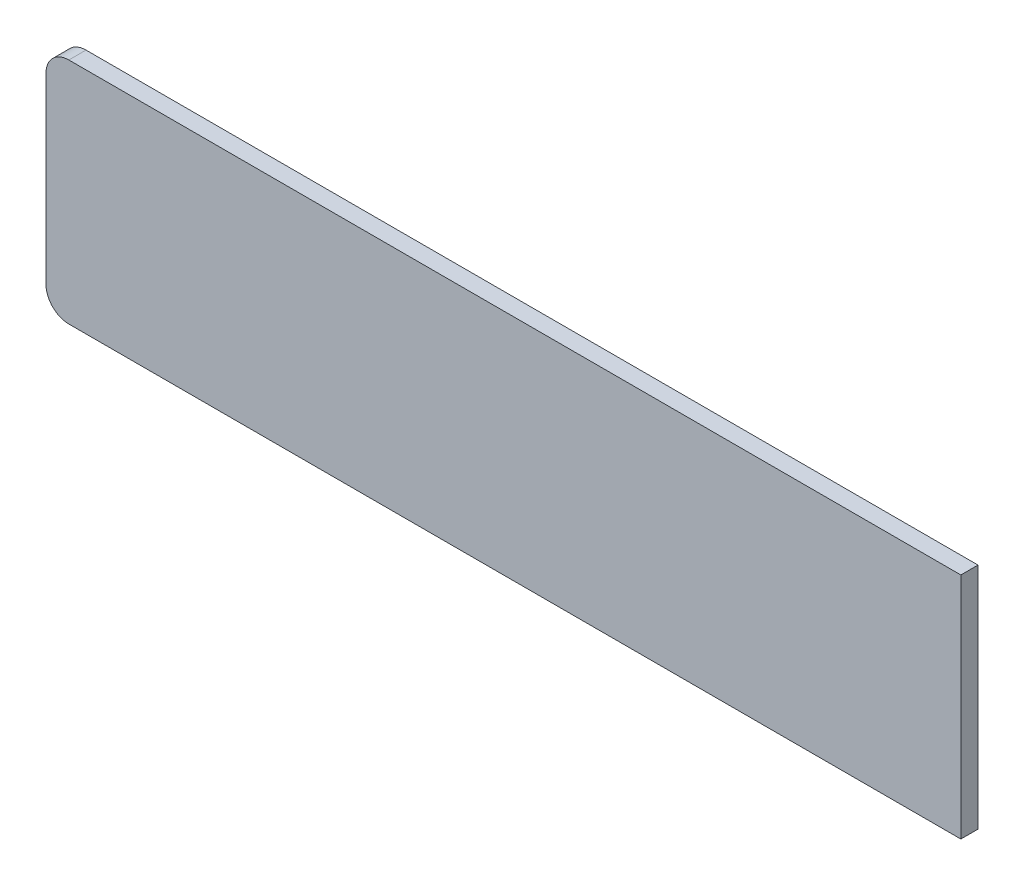
SolidWorks part; units mm, degrees
material "Просиликоненая ткань"
ref_plane "Спереди" through (0, 0, 0) normal (0, 0, 1) x (1, 0, 0)
ref_plane "Сверху" through (0, 0, 0) normal (0, 1, 0) x (1, 0, 0)
ref_plane "Справа" through (0, 0, 0) normal (1, 0, 0) x (0, 0, -1)
sketch "Эскиз1" plane through (0, 0, 0) normal (0, 0, 1) x (1, 0, 0)
  line L1 (-92.9515, 44.1657) -> (-14.9515, 44.1657)
  line L2 (-94.9515, 42.1657) -> (-94.9515, 26.1657)
  line L3 (-92.9515, 24.1657) -> (-14.9515, 24.1657)
  line L4 (-14.9515, 44.1657) -> (-14.9515, 24.1657)
  line L5 (-94.9515, 44.1657) -> (-14.9515, 24.1657) construction
  line L6 (-94.9515, 24.1657) -> (-14.9515, 44.1657) construction
  arc A0 (-92.9515, 24.1657) -> (-94.9515, 26.1657) centre (-92.9515, 26.1657) cw
  arc A1 (-92.9515, 44.1657) -> (-94.9515, 42.1657) centre (-92.9515, 42.1657) ccw
  point P0 (-54.9515, 34.1657)
  dimension "D1" = 2
extrude "Бобышка-Вытянуть1" add sketch "Эскиз1" along normal blind 1.5
